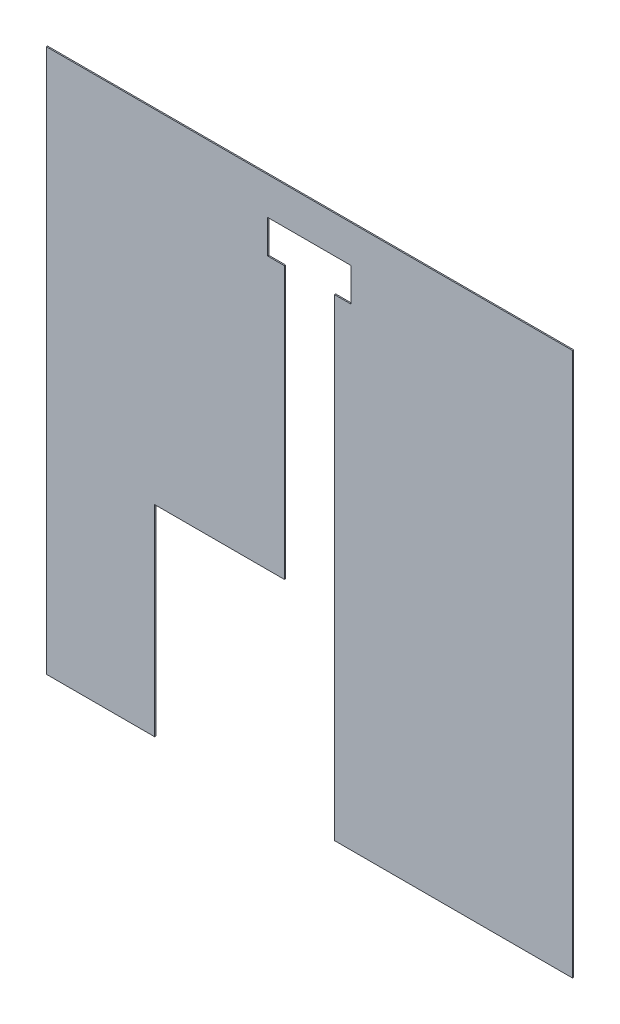
SolidWorks part; units mm, degrees
ref_plane "Alzado" through (0, 0, 0) normal (0, 0, 1) x (1, 0, 0)
ref_plane "Planta" through (0, 0, 0) normal (0, 1, 0) x (1, 0, 0)
ref_plane "Vista lateral" through (0, 0, 0) normal (1, 0, 0) x (0, 0, -1)
sketch "Croquis1" plane through (0, 0, 0) normal (0, 0, 1) x (1, 0, 0)
  line L1 (0, 0) -> (1258.4, 0)
  line L2 (0, 0) -> (0, -1300)
  line L3 (0, -1300) -> (1258.4, -1300)
  line L4 (1258.4, 0) -> (1258.4, -1300)
  dimension "D1" = 1258.4
  dimension "D2" = 1300
extrude "Saliente-Extruir1" add sketch "Croquis1" along normal blind 2.9
sketch "Croquis2" plane through (0, 0, 2.9) normal (0, 0, 1) x (1, 0, 0)
  line L0 (629.2, 0) -> (629.2, -88.9) construction
  line L1 (1258.4, 0) -> (0, 0) construction
  line L2 (729.2, -88.9) -> (529.2, -88.9)
  line L3 (529.2, -88.9) -> (529.2, -168.9)
  line L4 (629.2, -88.9) -> (629.2, -446.2123) construction
  line L5 (529.2, -168.9) -> (729.2, -168.9)
  line L6 (729.2, -88.9) -> (729.2, -168.9)
  point P10 (629.2, -168.9)
  dimension "D1" = 88.9
  dimension "D2" = 100
  dimension "D3" = 80
extrude "Cortar-Extruir1" cut sketch "Croquis2" against normal blind 10
sketch "Croquis3" plane through (0, 0, 2.9) normal (0, 0, 1) x (1, 0, 0)
  line L0 (569.2, -168.9) -> (569.2, -818.9)
  line L1 (529.2, -168.9) -> (729.2, -168.9) construction
  line L2 (569.2, -818.9) -> (259.2, -818.9)
  line L3 (259.2, -818.9) -> (259.2, -1300)
  line L5 (0, -1300) -> (1258.4, -1300) construction
  line L6 (259.2, -1300) -> (689.2, -1300)
  line L7 (689.2, -1300) -> (689.2, -168.9)
  line L8 (729.2, -168.9) -> (729.2, -88.9) construction
  line L9 (529.2, -88.9) -> (529.2, -168.9) construction
  line L10 (569.2, -168.9) -> (689.2, -168.9)
  dimension "D1" = 430
  dimension "D2" = 40
  dimension "D3" = 40
  dimension "D4" = 650
extrude "Cortar-Extruir2" cut sketch "Croquis3" against normal blind 3
